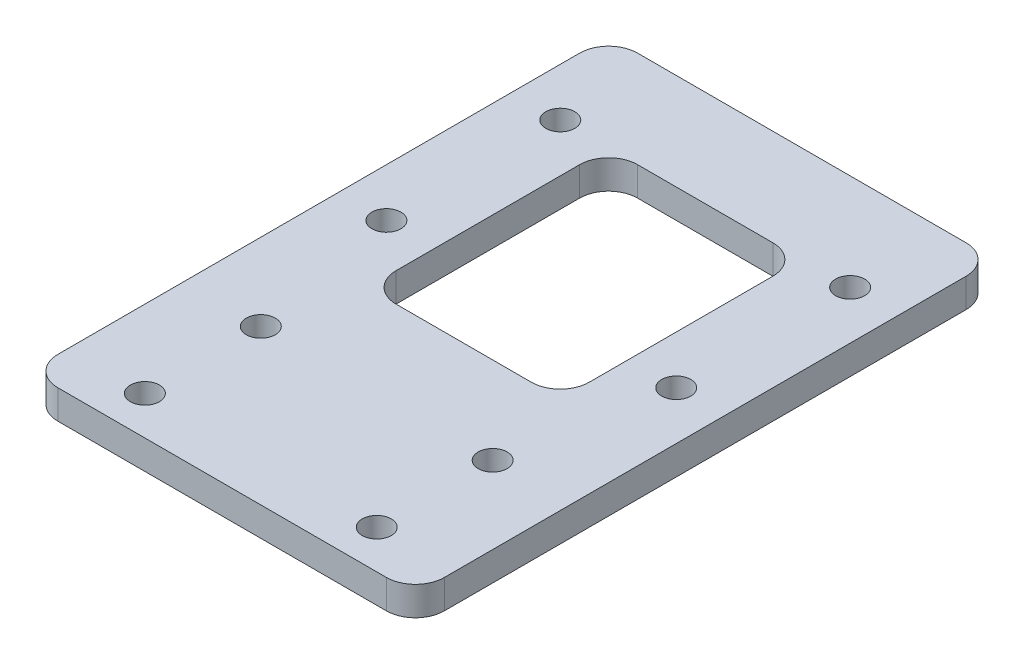
SolidWorks part; units mm, degrees
material "Thornel Mat VMA"
ref_plane "前视基准面" through (0, 0, 0) normal (0, 0, 1) x (1, 0, 0)
ref_plane "上视基准面" through (0, 0, 0) normal (0, 1, 0) x (1, 0, 0)
ref_plane "右视基准面" through (0, 0, 0) normal (1, 0, 0) x (0, 0, -1)
sketch "草图1" plane through (0, 0, 0) normal (0, 1, 0) x (1, 0, 0)
  line L0 (-17.902, -29.3674) -> (22.098, -29.3674)
  line L5 (22.098, 30.6326) -> (-17.902, 30.6326)
  line L6 (-17.902, 30.6326) -> (-17.902, -29.3674)
  line L7 (22.098, 30.6326) -> (22.098, -29.3674)
  circle A0 centre (14.098, -25.3674) radius 1.5
  circle A1 centre (-9.902, -25.3674) radius 1.5
  circle A2 centre (14.098, -13.3674) radius 1.5
  circle A3 centre (-9.902, -13.3674) radius 1.5
  circle A4 centre (17.098, 2.6326) radius 1.5
  circle A5 centre (-12.902, 2.6326) radius 1.5
  circle A6 centre (17.098, 20.6326) radius 1.5
  circle A7 centre (-12.902, 20.6326) radius 1.5
  dimension "D1" = 40
extrude "凸台-拉伸1" add sketch "草图1" along normal blind 3
fillet "圆角1" radius 3 4 edges at (-17.902, 1.5, -30.6326) (22.098, 1.5, -30.6326) (22.098, 1.5, 29.3674) (-17.902, 1.5, 29.3674)
sketch "草图5" plane through (0, 3, 0) normal (0, 1, 0) x (1, 0, 0)
  line L0 (19.098, 30.6326) -> (-14.902, 30.6326) construction
  line L1 (-7.902, 20.6326) -> (12.098, 20.6326)
  line L2 (-7.902, 20.6326) -> (-7.902, -4.3674)
  line L3 (-7.902, -4.3674) -> (12.098, -4.3674)
  line L4 (12.098, 20.6326) -> (12.098, -4.3674)
  line L5 (22.098, -26.3674) -> (22.098, 27.6326) construction
  dimension "D1" = 20
  dimension "D2" = 25
  dimension "D3" = 10
  dimension "D4" = 10
extrude "切除-拉伸1" cut sketch "草图5" against normal through all
fillet "圆角2" radius 3 4 edges at (-7.902, 1.5, 4.3674) (12.098, 1.5, 4.3674) (12.098, 1.5, -20.6326) (-7.902, 1.5, -20.6326)
